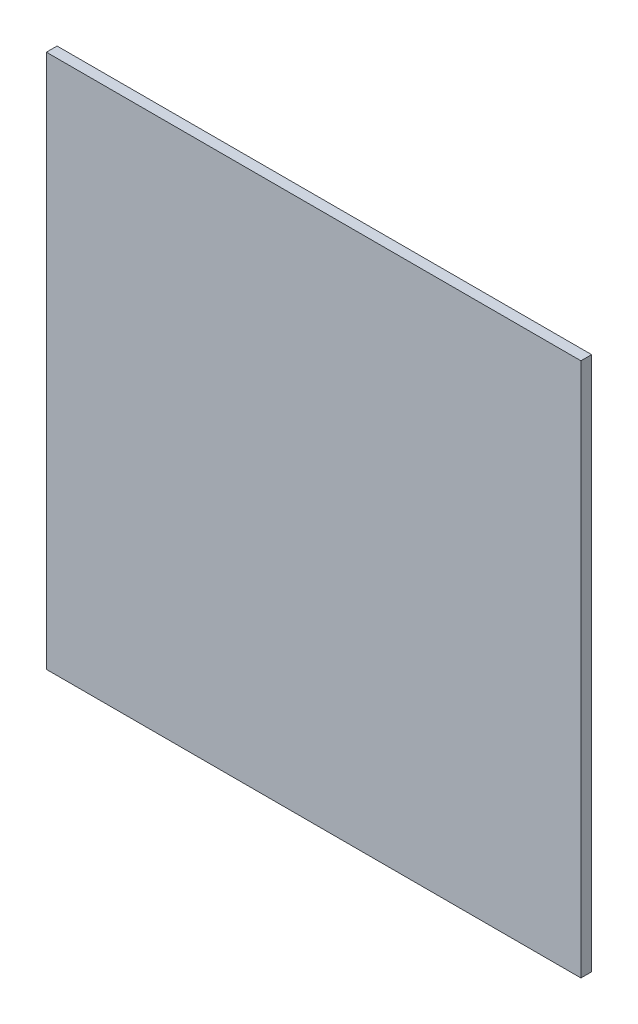
SolidWorks part; units mm, degrees
ref_plane "Front Plane" through (0, 0, 0) normal (0, 0, 1) x (1, 0, 0)
ref_plane "Top Plane" through (0, 0, 0) normal (0, 1, 0) x (1, 0, 0)
ref_plane "Right Plane" through (0, 0, 0) normal (1, 0, 0) x (0, 0, -1)
sketch "Sketch1" plane through (0, 0, 0) normal (0, 0, 1) x (1, 0, 0)
  line L1 (50, -50) -> (-50, -50)
  line L2 (50, -50) -> (50, 50)
  line L3 (50, 50) -> (-50, 50)
  line L4 (-50, -50) -> (-50, 50)
  line L5 (50, -50) -> (-50, 50) construction
  line L6 (50, 50) -> (-50, -50) construction
  point P0 (0, 0)
  dimension "D1" = 100
  dimension "D2" = 100
extrude "Boss-Extrude1" add sketch "Sketch1" along normal blind 2
